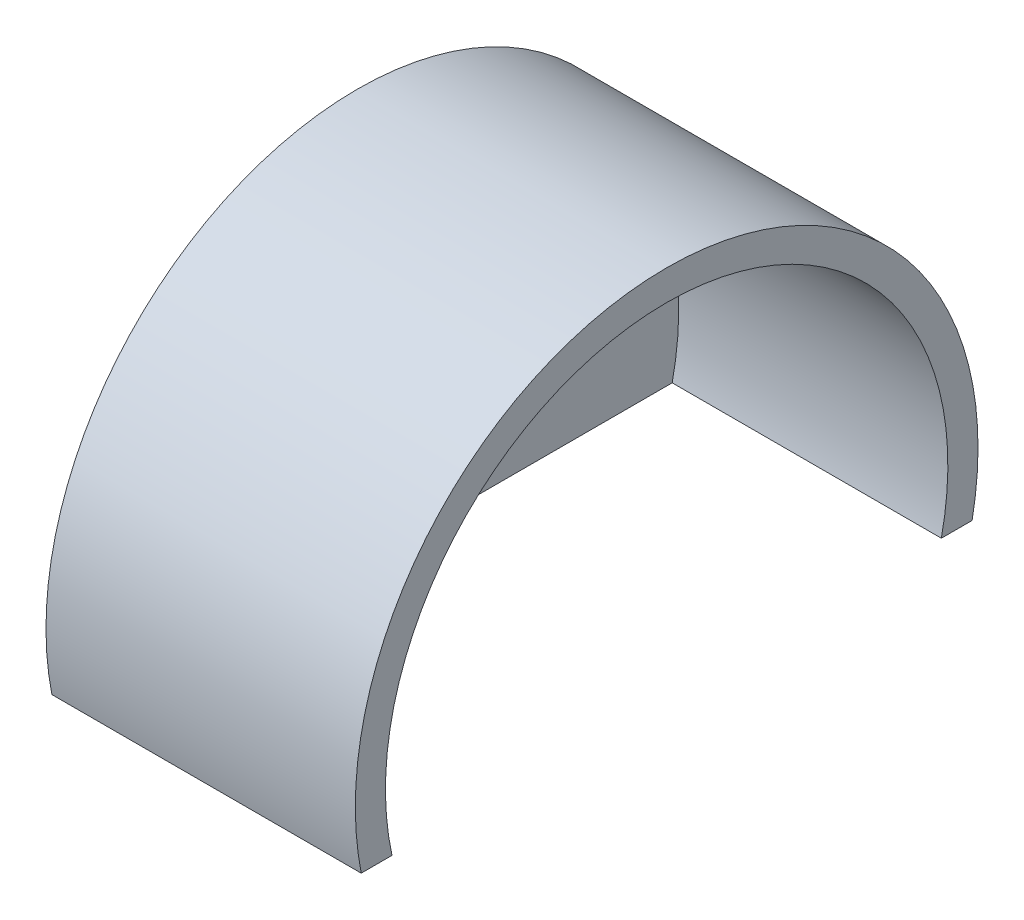
SolidWorks part; units mm, degrees
material "1060 合金"
ref_plane "前视基准面" through (0, 0, 0) normal (0, 0, 1) x (1, 0, 0)
ref_plane "上视基准面" through (0, 0, 0) normal (0, 1, 0) x (1, 0, 0)
ref_plane "右视基准面" through (0, 0, 0) normal (1, 0, 0) x (0, 0, -1)
sketch "草图1" plane through (0, 0, 0) normal (1, 0, 0) x (0, 0, -1)
  line L0 (-30.4138, -6) -> (30.4138, -6)
  line L1 (0, 0) -> (44.4957, 0) construction
  circle A0 centre (0, 0) radius 26 construction
  arc A1 (30.4138, -6) -> (-30.4138, -6) centre (0, 0) ccw
  circle A2 centre (0, 0) radius 31 construction
  dimension "D1" = 52
  dimension "D3" = 6
  dimension "D2" = 5
extrude "凸台-拉伸1" add sketch "草图1" along normal blind 4
sketch "草图2" plane through (4, 0, 0) normal (1, 0, 0) x (0, 0, -1)
  line L0 (-30.4138, -6) -> (30.4138, -6) construction
  line L1 (-30.4138, -6) -> (-27.3496, -6)
  line L2 (27.3496, -6) -> (30.4138, -6)
  arc A1 (30.4138, -6) -> (-30.4138, -6) centre (0, 0) ccw construction
  arc A2 (30.4138, -6) -> (-30.4138, -6) centre (0, 0) ccw
  arc A3 (27.3496, -6) -> (-27.3496, -6) centre (0, 0) ccw
  dimension "D1" = 3
extrude "凸台-拉伸2" add sketch "草图2" along normal blind 26.8
